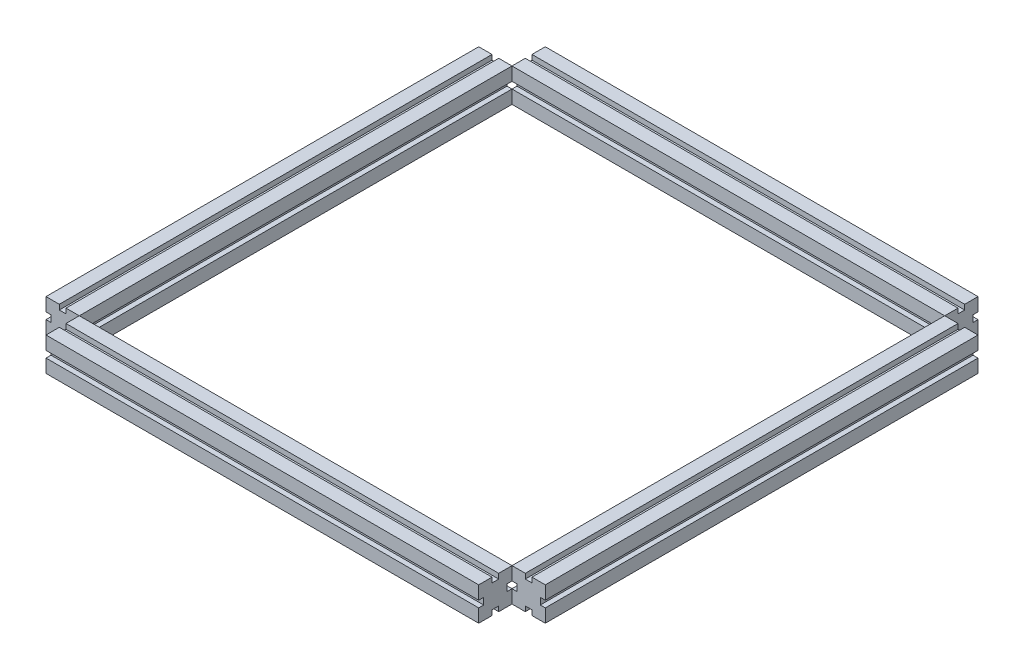
SolidWorks part; units mm, degrees
ref_plane "Front Plane" through (0, 0, 0) normal (0, 0, 1) x (1, 0, 0)
ref_plane "Top Plane" through (0, 0, 0) normal (0, 1, 0) x (1, 0, 0)
ref_plane "Right Plane" through (0, 0, 0) normal (1, 0, 0) x (0, 0, -1)
sketch "Sketch2" plane through (0, 0, 0) normal (0, 1, 0) x (1, 0, 0)
  line L1 (-280, 280) -> (280, 280)
  line L2 (-280, 280) -> (-280, -280)
  line L3 (-280, -280) -> (280, -280)
  line L4 (280, 280) -> (280, -280)
  line L5 (-280, 280) -> (280, -280) construction
  line L6 (-280, -280) -> (280, 280) construction
  point P0 (0, 0)
  dimension "D1" = 560
  dimension "D2" = 45
sketch "Sketch4" plane through (0, 0, 0) normal (0, 0, 1) x (1, 0, 0)
  line L0 (-280, 0) -> (280, 0) construction
  line L1 (300, -20) -> (284, -20)
  line L2 (300, -20) -> (300, -4)
  line L3 (300, 20) -> (284, 20)
  line L4 (260, -20) -> (260, -4)
  line L5 (300, -20) -> (260, 20) construction
  line L6 (300, 20) -> (260, -20) construction
  line L7 (-280, 0) -> (280, 0) construction
  line L9 (0, -55) -> (0, 55) construction
  line L10 (-266, 0) -> (-280, 0) construction
  line L15 (300, 0) -> (294, 0) construction
  line L16 (294, 4) -> (294, -4)
  line L17 (294, -4) -> (300, -4)
  line L18 (294, 4) -> (300, 4)
  line L19 (276, -14) -> (276, -20)
  line L20 (284, -14) -> (276, -14)
  line L21 (284, -14) -> (284, -20)
  line L22 (266, 4) -> (260, 4)
  line L23 (266, -4) -> (266, 4)
  line L24 (266, -4) -> (260, -4)
  line L25 (284, 14) -> (284, 20)
  line L26 (276, 14) -> (284, 14)
  line L27 (276, 14) -> (276, 20)
  line L28 (300, 4) -> (300, 20)
  line L29 (276, -20) -> (260, -20)
  line L30 (260, 4) -> (260, 20)
  line L31 (276, 20) -> (260, 20)
  line L32 (280, 14) -> (280, 0) construction
  line L33 (280, 0) -> (280, -14) construction
  line L34 (266, 0) -> (280, 0) construction
  line L35 (-280, 0) -> (-280, -14) construction
  line L36 (-280, 14) -> (-280, 0) construction
  line L37 (-300, 0) -> (-294, 0) construction
  line L38 (-300, 20) -> (-260, -20) construction
  line L39 (-300, -20) -> (-260, 20) construction
  line L40 (-276, 20) -> (-260, 20)
  line L41 (-260, 4) -> (-260, 20)
  line L42 (-276, -20) -> (-260, -20)
  line L43 (-300, 4) -> (-300, 20)
  line L44 (-276, 14) -> (-276, 20)
  line L45 (-276, 14) -> (-284, 14)
  line L46 (-284, 14) -> (-284, 20)
  line L47 (-266, -4) -> (-260, -4)
  line L48 (-266, -4) -> (-266, 4)
  line L49 (-266, 4) -> (-260, 4)
  line L50 (-284, -14) -> (-284, -20)
  line L51 (-284, -14) -> (-276, -14)
  line L52 (-276, -14) -> (-276, -20)
  line L53 (-294, 4) -> (-300, 4)
  line L54 (-294, -4) -> (-300, -4)
  line L55 (-294, 4) -> (-294, -4)
  line L56 (-260, -20) -> (-260, -4)
  line L57 (-300, 20) -> (-284, 20)
  line L58 (-300, -20) -> (-300, -4)
  line L59 (-300, -20) -> (-284, -20)
  point P0 (280, 0)
  point P23 (294, 0)
  point P40 (280, 0)
  dimension "D1" = 40
  dimension "D2" = 40
  dimension "D3" = 6
  dimension "D4" = 8
  dimension "D5" = 6
  dimension "D6" = 8
  dimension "D7" = 8
  dimension "D8" = 6
  dimension "D9" = 8
  dimension "D10" = 6
extrude "Boss-Extrude2" add sketch "Sketch4" along normal up to vertex (280 mm away) and the other way up to vertex (280 mm away) up to point (280, 0, 280) other way up to point (280, 0, -280)
sketch "Sketch5" plane through (0, 0, 0) normal (1, 0, 0) x (0, 0, -1)
  line L1 (300, -20) -> (284, -20)
  line L2 (300, -20) -> (300, -4)
  line L3 (300, 20) -> (284, 20)
  line L4 (260, -20) -> (260, -4)
  line L5 (300, -20) -> (260, 20) construction
  line L6 (300, 20) -> (260, -20) construction
  line L7 (0, 55) -> (0, -55) construction
  line L8 (-280, 0) -> (-280, 20) construction
  line L13 (300, 0) -> (280, 0) construction
  line L14 (280, 0) -> (260, 0) construction
  line L15 (280, -20) -> (280, 0) construction
  line L16 (280, 0) -> (280, 20) construction
  line L17 (294, 4) -> (294, -4)
  line L18 (294, -4) -> (300, -4)
  line L19 (294, 4) -> (300, 4)
  line L20 (266, 4) -> (266, -4)
  line L21 (266, -4) -> (260, -4)
  line L22 (266, 4) -> (260, 4)
  line L23 (284, -14) -> (276, -14)
  line L24 (276, -14) -> (276, -20)
  line L25 (284, -14) -> (284, -20)
  line L26 (284, 14) -> (276, 14)
  line L27 (276, 14) -> (276, 20)
  line L28 (284, 14) -> (284, 20)
  line L29 (300, 4) -> (300, 20)
  line L30 (276, -20) -> (260, -20)
  line L31 (260, 4) -> (260, 20)
  line L32 (276, 20) -> (260, 20)
  line L33 (-280, -20) -> (-280, 0) construction
  line L34 (-280, 0) -> (-260, 0) construction
  line L35 (-300, 0) -> (-280, 0) construction
  line L36 (-300, 20) -> (-260, -20) construction
  line L37 (-300, -20) -> (-260, 20) construction
  line L38 (-276, 20) -> (-260, 20)
  line L39 (-260, 4) -> (-260, 20)
  line L40 (-276, -20) -> (-260, -20)
  line L41 (-300, 4) -> (-300, 20)
  line L42 (-284, 14) -> (-284, 20)
  line L43 (-276, 14) -> (-276, 20)
  line L44 (-284, 14) -> (-276, 14)
  line L45 (-284, -14) -> (-284, -20)
  line L46 (-276, -14) -> (-276, -20)
  line L47 (-284, -14) -> (-276, -14)
  line L48 (-266, 4) -> (-260, 4)
  line L49 (-266, -4) -> (-260, -4)
  line L50 (-266, 4) -> (-266, -4)
  line L51 (-294, 4) -> (-300, 4)
  line L52 (-294, -4) -> (-300, -4)
  line L53 (-294, 4) -> (-294, -4)
  line L54 (-260, -20) -> (-260, -4)
  line L55 (-300, 20) -> (-284, 20)
  line L56 (-300, -20) -> (-300, -4)
  line L57 (-300, -20) -> (-284, -20)
  point P0 (280, 0)
  point P23 (294, 0)
  point P28 (266, 0)
  point P33 (280, -14)
  point P38 (280, 14)
  point P64 (-280, 14)
  point P65 (-280, -14)
  point P66 (-266, 0)
  point P67 (-294, 0)
  dimension "D1" = 40
  dimension "D2" = 40
  dimension "D3" = 6
  dimension "D4" = 8
  dimension "D5" = 8
  dimension "D6" = 6
  dimension "D7" = 6
  dimension "D8" = 8
  dimension "D9" = 8
  dimension "D10" = 6
extrude "Boss-Extrude3" add sketch "Sketch5" along normal up to vertex (280 mm away) and the other way up to vertex (280 mm away) up to point (280, 0, -280) other way up to point (-280, 0, -280)
sketch "Sketch6" plane through (0, 0, 0) normal (0, 1, 0) x (1, 0, 0)
  line L1 (-300, 300) -> (-260, 300)
  line L2 (-300, 300) -> (-300, 260)
  line L3 (-300, 260) -> (-260, 260)
  line L4 (-260, 300) -> (-260, 260)
  line L5 (280, 300) -> (-280, 300) construction
  line L6 (-55, 0) -> (55, 0) construction
  line L7 (-260, -300) -> (-260, -260)
  line L8 (-300, -260) -> (-260, -260)
  line L9 (-300, -300) -> (-300, -260)
  line L10 (-300, -300) -> (-260, -300)
  line L11 (0, -55) -> (0, 55) construction
  line L12 (300, -300) -> (260, -300)
  line L13 (300, -300) -> (300, -260)
  line L14 (300, -260) -> (260, -260)
  line L15 (260, -300) -> (260, -260)
  line L16 (260, 300) -> (260, 260)
  line L17 (300, 260) -> (260, 260)
  line L18 (300, 300) -> (300, 260)
  line L19 (300, 300) -> (260, 300)
  line L22 (-300, -280) -> (-300, 280) construction
  dimension "D1" = 40
  dimension "D2" = 40
extrude "Cut-Extrude1" cut sketch "Sketch6" against normal through all both and the other way through all
